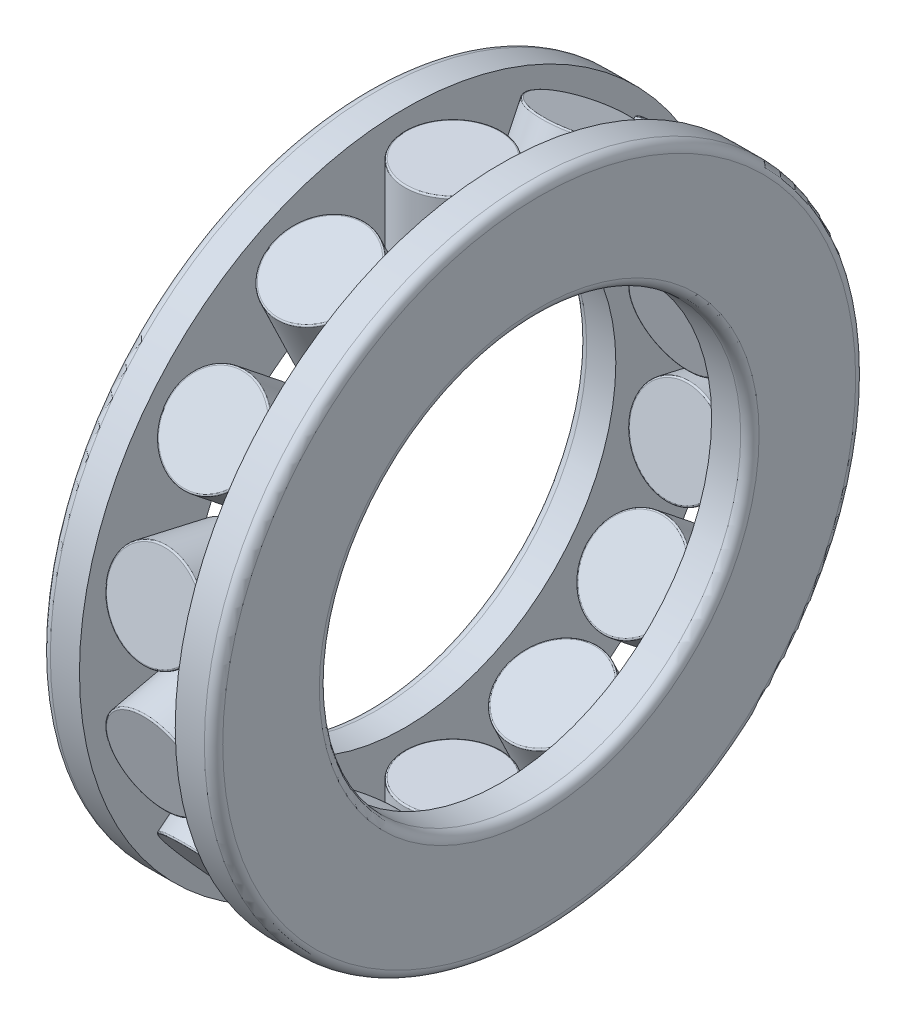
SolidWorks part; units mm, degrees
ref_plane "Plane1" through (0, 0, 0) normal (0, 0, 1) x (1, 0, 0)
ref_plane "Plane2" through (0, 0, 0) normal (0, 1, 0) x (1, 0, 0)
ref_plane "Plane3" through (0, 0, 0) normal (1, 0, 0) x (0, 0, -1)
sketch "Clipboard" plane through (0, 0, 0) normal (0, 0, 1) x (1, 0, 0)
  line L0 (-10, 0) -> (10, 0) construction
  line L1 (0, 0) -> (21.6965, -5.4095)
  line L2 (0, 0) -> (27.3662, 35.0271)
  line L3 (0, 0) -> (13.7666, -17.6205)
  line L4 (0, 0) -> (-22.3471, -0.7804)
  dimension "BallCLRad" = 44.45
  dimension "Count" = 52
  dimension "Show_count" = 52
  dimension "Max_count" = 14
  dimension "Min_count" = 2
sketch "InnRacSke" plane through (0, 0, 0) normal (0, 0, 1) x (1, 0, 0)
  line L1 (-7.9375, 34.925) -> (-12.7635, 34.925)
  line L2 (-14.2875, 36.449) -> (-14.2875, 52.451)
  line L3 (-12.7635, 53.975) -> (-7.9375, 53.975)
  line L4 (-7.9375, 53.975) -> (-7.9375, 34.925)
  line L5 (-34.925, 0) -> (34.925, 0) construction
  line L6 (0, 0) -> (0, 25.4) construction
  arc A0 (-12.7635, 34.925) -> (-14.2875, 36.449) centre (-12.7635, 36.449) cw
  arc A1 (-14.2875, 52.451) -> (-12.7635, 53.975) centre (-12.7635, 52.451) cw
  dimension "ID" = 69.85
  dimension "OD" = 107.95
  dimension "Width" = 28.575
  dimension "gap" = 15.875
revolve "Race" add sketch "InnRacSke" angle 360 about L5
ref_axis "Axis1" through (-50, 0, 0) along (1, 0, 0)
sketch "RolDetSke" plane through (0, 0, 0) normal (0, 0, 1) x (1, 0, 0)
  line L0 (0, 33.02) -> (0, 55.88) construction
  line L3 (0, 50.8) -> (7.7232, 50.8)
  line L4 (0, 50.8) -> (0, 38.1)
  line L5 (0, 38.1) -> (7.7232, 38.1)
  line L6 (7.9772, 50.546) -> (7.9772, 38.354)
  arc A0 (7.9772, 38.354) -> (7.7232, 38.1) centre (7.7232, 38.354) cw
  arc A1 (7.7232, 50.8) -> (7.9772, 50.546) centre (7.7232, 50.546) cw
  dimension "D1" = 0.254
  dimension "Roller_diameter" = 15.9544
  dimension "Cyl_Len" = 12.7
  dimension "offset" = 38.1
revolve "RollerDetailed" add sketch "RolDetSke" angle 360 about L0
sketch "RolSimSke" plane through (0, 0, 0) normal (0, 0, 1) x (1, 0, 0)
  line L1 (-17.78, 0) -> (12.7, 0) construction
  line L3 (-7.7232, 50.8) -> (7.7232, 50.8)
  line L4 (-7.9772, 50.546) -> (-7.9772, 38.354)
  line L5 (-7.7232, 38.1) -> (7.7232, 38.1)
  line L6 (7.9772, 50.546) -> (7.9772, 38.354)
  arc A0 (-7.9772, 38.354) -> (-7.7232, 38.1) centre (-7.7232, 38.354) ccw
  arc A1 (-7.7232, 50.8) -> (-7.9772, 50.546) centre (-7.7232, 50.546) ccw
  arc A2 (7.9772, 50.546) -> (7.7232, 50.8) centre (7.7232, 50.546) ccw
  arc A3 (7.7232, 38.1) -> (7.9772, 38.354) centre (7.7232, 38.354) ccw
  dimension "Roller_diameter" = 15.9544
  dimension "Cyl_Len" = 12.7
  dimension "offset" = 38.1
  dimension "Rol_rad" = 0.254
  dimension "Halfdia" = 7.9772
revolve "RollersSimplified" [suppressed] add sketch "RolSimSke" angle 360 about L1
mirror "Mirror1" about plane through (0, 0, 0) normal (1, 0, 0) of "Race"
pattern_circular "RollersDetailed" count 14 every 25.714 about axis through (-50, 0, 0) along (1, 0, 0) of "RollerDetailed"
sketch "CagSpiSke" plane through (0, 0, 0) normal (0, 0, 1) x (1, 0, 0)
  line L0 (2.3932, 35.6235) -> (2.3932, 52.8955)
  line L1 (2.3932, 52.8955) -> (-2.3932, 52.8955)
  line L2 (-2.3932, 35.6235) -> (-2.3932, 52.8955)
  line L3 (-2.3932, 35.6235) -> (2.3932, 35.6235)
  line L4 (-34.925, 0) -> (34.925, 0) construction
  line L5 (0, 0) -> (0, 64.3918) construction
  dimension "ID" = 71.247
  dimension "OD" = 105.791
  dimension "Thickness" = 4.7863
revolve "CageSpine" [suppressed] add sketch "CagSpiSke" angle 360 about L4
equation "\"BallCLRad@Clipboard\" =  ( \"OD@InnRacSke\" + \"ID@InnRacSke\" )  / 4"
equation "\"offset@RolDetSke\" = \"BallCLRad@Clipboard\" - \"Cyl_Len@RolDetSke\" / 2"
equation "\"Cyl_Len@RolSimSke\" = \"Cyl_Len@RolDetSke\""
equation "\"offset@RolSimSke\" = \"BallCLRad@Clipboard\" - \"Cyl_Len@RolSimSke\" / 2"
equation "\"Roller_diameter@RolDetSke\" = \"gap@InnRacSke\" * 1.005"
equation "\"Roller_diameter@RolSimSke\" = \"gap@InnRacSke\" * 1.005"
equation "\"Max_count@Clipboard\" = int( 3.14159265 / atn(( \"Roller_diameter@RolDetSke\" / 2) / sqr( \"offset@RolDetSke\"  *  \"offset@RolDetSke\" - ( \"Roller_diameter@RolDetSke\" / 2) *  ( \"Roller_diameter@RolDetSke\" / 2))))"
equation "\"Max_count@Clipboard\" = ((sgn( \"Max_count@Clipboard\" - \"Count@Clipboard\" )-1)*( \"Max_count@Clipboard\" - \"Count@Clipboard\" ))/-2+ \"Count@Clipboard\""
equation "\"Count@RollersDetailed\" = int( \"Show_count@Clipboard\" ) "
equation "\"Count@RollersDetailed\" = ((sgn( \"Count@RollersDetailed\" - \"Max_count@Clipboard\" )-1)*( \"Count@RollersDetailed\" - \"Max_count@Clipboard\" ))/-2+ \"Max_count@Clipboard\""
equation "\"Count@RollersDetailed\" = ((sgn( \"Count@RollersDetailed\" - \"Min_count@Clipboard\" )+1)*( \"Count@RollersDetailed\" - \"Min_count@Clipboard\"))/2 +\"Min_count@Clipboard\""
equation "\"Angle@RollersDetailed\" = 360.0 / \"Max_count@Clipboard\""
equation "\"Angle@CageSpine\" =  \"Angle@RollersDetailed\" * ( \"Count@RollersDetailed\" -1 + int( \"Count@RollersDetailed\" / \"Max_count@Clipboard\" ) )  + 0.001 -  int( \"Count@RollersDetailed\" / \"Max_count@Clipboard\" ) * 0.001"
equation "\"Angle@CageSpine\" =  \"Angle@CageSpine\" * int( \"Min_count@Clipboard\" / 2) + int(1 / \"Min_count@Clipboard\")  * 0.001"
equation "\"Thickness@CagSpiSke\" =  \"Roller_diameter@RolDetSke\" * 0.3"
equation "\"OD@CagSpiSke\" = \"OD@InnRacSke\" * 0.98"
equation "\"ID@CagSpiSke\" = \"ID@InnRacSke\" * 1.02"
equation "\"Halfdia@RolSimSke\" = \"Roller_diameter@RolSimSke\" / 2"
